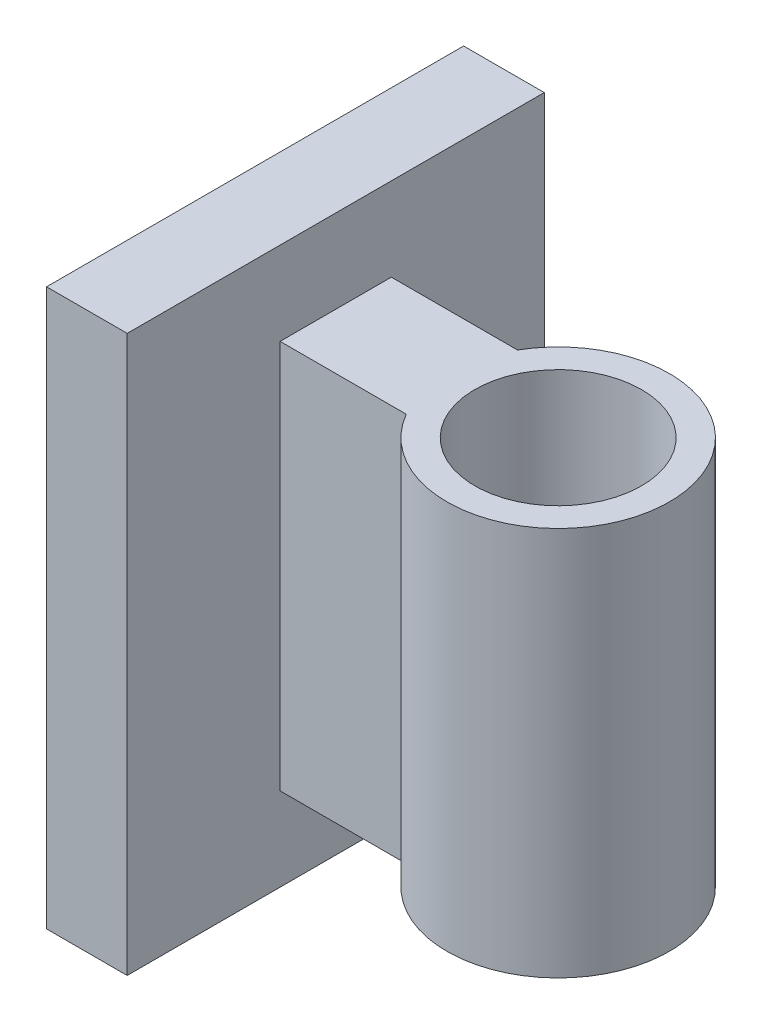
SolidWorks part; units mm, degrees
material "1023 Carbon Steel Sheet (SS)"
ref_plane "Front Plane" through (0, 0, 0) normal (0, 0, 1) x (1, 0, 0)
ref_plane "Top Plane" through (0, 0, 0) normal (0, 1, 0) x (1, 0, 0)
ref_plane "Right Plane" through (0, 0, 0) normal (1, 0, 0) x (0, 0, -1)
sketch "Sketch1" plane through (0, 0, 0) normal (1, 0, 0) x (0, 0, -1)
  line L1 (0, 0) -> (15, 0)
  line L2 (0, 0) -> (0, 20)
  line L3 (0, 20) -> (15, 20)
  line L4 (15, 0) -> (15, 20)
  dimension "D1" = 20
  dimension "D2" = 15
extrude "Boss-Extrude1" add sketch "Sketch1" along normal blind 2.9
ref_plane "Plane1" through (10.9, 0, 0) normal (1, 0, 0) x (0, 0, -1)
sketch "Sketch2" plane through (10.9, 0, 0) normal (1, 0, 0) x (0, 0, -1)
  line L0 (7.5, 0) -> (7.5, 51.7386) construction
  line L1 (0, 0) -> (15, 0) construction
  line L3 (11.5, 17) -> (11.5, 3)
  line L4 (11.5, 3) -> (10.5, 3)
  line L5 (10.5, 3) -> (10.5, 17)
  line L6 (10.5, 17) -> (11.5, 17)
  line L7 (15, 20) -> (0, 20) construction
  dimension "D1" = 3
  dimension "D2" = 4
  dimension "D3" = 3
  dimension "D4" = 3
revolve "Revolve1" add sketch "Sketch2" angle 360 about L0
sketch "Sketch4" plane through (2.9, 0, 0) normal (1, 0, 0) x (0, 0, -1)
  line L0 (3.5, 3) -> (11.5, 3) construction
  line L1 (5.5, 3) -> (9.5, 3)
  line L2 (5.5, 3) -> (5.5, 17)
  line L4 (9.5, 3) -> (9.5, 17)
  line L6 (11.5, 17) -> (3.5, 17) construction
  line L7 (9.5, 17) -> (5.5, 17)
  line L8 (11.5, 3) -> (11.5, 17) construction
  dimension "D1" = 2
  dimension "D2" = 2
extrude "Boss-Extrude2" add sketch "Sketch4" along normal up to surface (4.5359 mm away)
